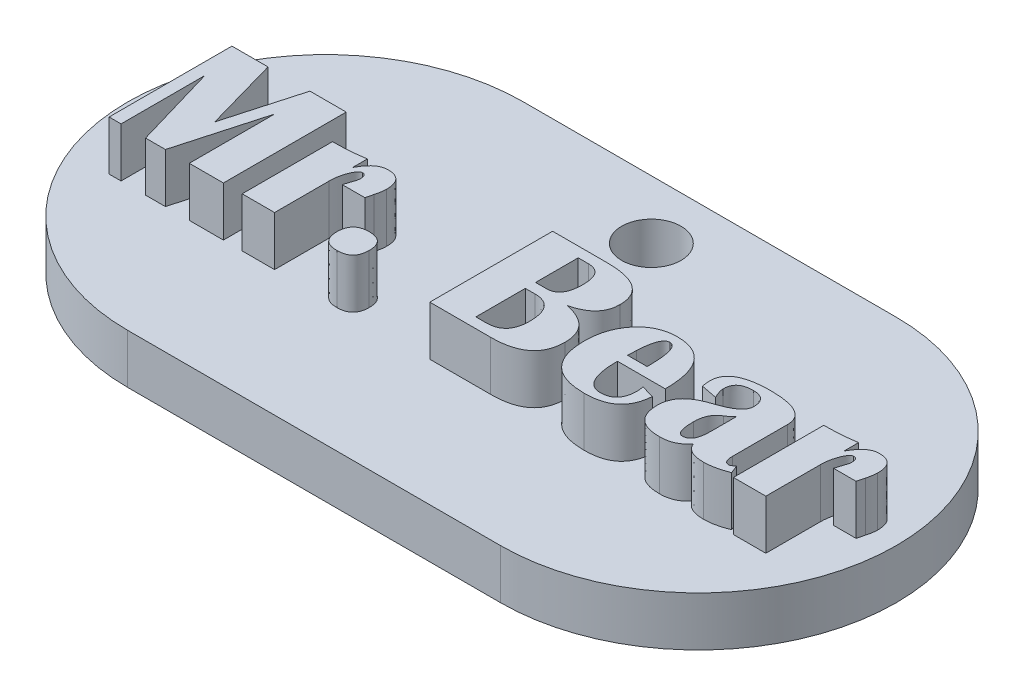
SolidWorks part; units mm, degrees
ref_plane "Front Plane" through (0, 0, 0) normal (0, 0, 1) x (1, 0, 0)
ref_plane "Top Plane" through (0, 0, 0) normal (0, 1, 0) x (1, 0, 0)
ref_plane "Right Plane" through (0, 0, 0) normal (1, 0, 0) x (0, 0, -1)
sketch "Sketch1" plane through (0, 0, 0) normal (0, 1, 0) x (1, 0, 0)
  line L0 (-9.4227, 0) -> (9.4227, 0) construction
  line L1 (-9.4227, 10) -> (9.4227, 10)
  line L2 (-9.4227, -10) -> (9.4227, -10)
  arc A0 (-9.4227, 10) -> (-9.4227, -10) centre (-9.4227, 0) ccw
  arc A1 (9.4227, -10) -> (9.4227, 10) centre (9.4227, 0) ccw
  point P3 (0, 0)
extrude "Boss-Extrude1" add sketch "Sketch1" along normal blind 2.5
sketch "Sketch2" plane through (0, 2.5, 0) normal (0, 1, 0) x (1, 0, 0)
  text T0 "Mr. Bear" font "Britannic Bold" height in points 26
extrude "Boss-Extrude2" add sketch "Sketch2" along normal blind 2.5
sketch "Sketch3" plane through (0, 2.5, 0) normal (0, 1, 0) x (1, 0, 0)
  circle A0 centre (0, 7.0417) radius 1.5
extrude "Cut-Extrude1" cut sketch "Sketch3" against normal blind 5
